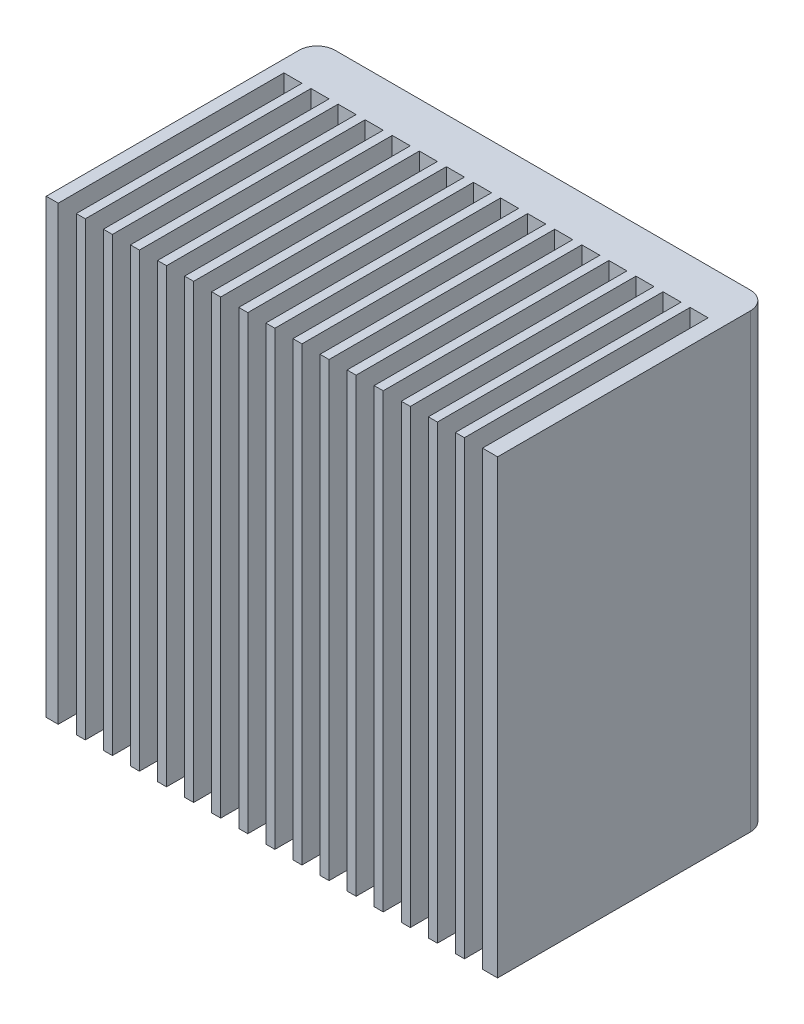
SolidWorks part; units mm, degrees
ref_plane "Front Plane" through (0, 0, 0) normal (0, 0, 1) x (1, 0, 0)
ref_plane "Top Plane" through (0, 0, 0) normal (0, 1, 0) x (1, 0, 0)
ref_plane "Right Plane" through (0, 0, 0) normal (1, 0, 0) x (0, 0, -1)
sketch "Sketch1" plane through (0, 0, 0) normal (0, 0, 1) x (1, 0, 0)
  circle A0 centre (0, 0) radius 10
extrude "Boss-Extrude1" add sketch "Sketch1" along normal blind 1
sketch "Sketch2" plane through (0, 0, 1) normal (0, 0, 1) x (1, 0, 0)
  line L1 (-25, 25) -> (25, 25)
  line L2 (-25, 25) -> (-25, -25)
  line L3 (-25, -25) -> (25, -25)
  line L4 (25, 25) -> (25, -25)
  line L5 (-25, 25) -> (25, -25) construction
  line L6 (-25, -25) -> (25, 25) construction
  point P0 (0, 0)
extrude "Boss-Extrude2" add sketch "Sketch2" along normal blind 30
sketch "Sketch3" plane through (0, 0, 31) normal (0, 0, 1) x (1, 0, 0)
  line L0 (25, 25) -> (-25, 25) construction
  line L1 (-23.6705, 25) -> (-21.6705, 25)
  line L2 (-23.6705, 25) -> (-23.6705, -25)
  line L3 (-23.6705, -25) -> (-21.6705, -25)
  line L4 (-21.6705, 25) -> (-21.6705, -25)
  line L5 (-25, -25) -> (25, -25) construction
  line L6 (-20.6705, 25) -> (-18.6705, 25)
  line L7 (-18.6705, 25) -> (-18.6705, -25)
  line L8 (-20.6705, 25) -> (-20.6705, -25)
  line L9 (-20.6705, -25) -> (-18.6705, -25)
  line L10 (-17.6705, 25) -> (-15.6705, 25)
  line L11 (-15.6705, 25) -> (-15.6705, -25)
  line L12 (-17.6705, 25) -> (-17.6705, -25)
  line L13 (-17.6705, -25) -> (-15.6705, -25)
  line L14 (-14.6705, 25) -> (-12.6705, 25)
  line L15 (-12.6705, 25) -> (-12.6705, -25)
  line L16 (-14.6705, 25) -> (-14.6705, -25)
  line L17 (-14.6705, -25) -> (-12.6705, -25)
  line L18 (-11.6705, 25) -> (-9.6705, 25)
  line L19 (-9.6705, 25) -> (-9.6705, -25)
  line L20 (-11.6705, 25) -> (-11.6705, -25)
  line L21 (-11.6705, -25) -> (-9.6705, -25)
  line L22 (-8.6705, 25) -> (-6.6705, 25)
  line L23 (-6.6705, 25) -> (-6.6705, -25)
  line L24 (-8.6705, 25) -> (-8.6705, -25)
  line L25 (-8.6705, -25) -> (-6.6705, -25)
  line L26 (-5.6705, 25) -> (-3.6705, 25)
  line L27 (-3.6705, 25) -> (-3.6705, -25)
  line L28 (-5.6705, 25) -> (-5.6705, -25)
  line L29 (-5.6705, -25) -> (-3.6705, -25)
  line L30 (-2.6705, 25) -> (-0.6705, 25)
  line L31 (-0.6705, 25) -> (-0.6705, -25)
  line L32 (-2.6705, 25) -> (-2.6705, -25)
  line L33 (-2.6705, -25) -> (-0.6705, -25)
  line L34 (0.3295, 25) -> (2.3295, 25)
  line L35 (2.3295, 25) -> (2.3295, -25)
  line L36 (0.3295, 25) -> (0.3295, -25)
  line L37 (0.3295, -25) -> (2.3295, -25)
  line L38 (3.3295, 25) -> (5.3295, 25)
  line L39 (5.3295, 25) -> (5.3295, -25)
  line L40 (3.3295, 25) -> (3.3295, -25)
  line L41 (3.3295, -25) -> (5.3295, -25)
  line L42 (6.3295, 25) -> (8.3295, 25)
  line L43 (8.3295, 25) -> (8.3295, -25)
  line L44 (6.3295, 25) -> (6.3295, -25)
  line L45 (6.3295, -25) -> (8.3295, -25)
  line L46 (9.3295, 25) -> (11.3295, 25)
  line L47 (11.3295, 25) -> (11.3295, -25)
  line L48 (9.3295, 25) -> (9.3295, -25)
  line L49 (9.3295, -25) -> (11.3295, -25)
  line L50 (12.3295, 25) -> (14.3295, 25)
  line L51 (14.3295, 25) -> (14.3295, -25)
  line L52 (12.3295, 25) -> (12.3295, -25)
  line L53 (12.3295, -25) -> (14.3295, -25)
  line L54 (15.3295, 25) -> (17.3295, 25)
  line L55 (17.3295, 25) -> (17.3295, -25)
  line L56 (15.3295, 25) -> (15.3295, -25)
  line L57 (15.3295, -25) -> (17.3295, -25)
  line L58 (18.3295, 25) -> (20.3295, 25)
  line L59 (20.3295, 25) -> (20.3295, -25)
  line L60 (18.3295, 25) -> (18.3295, -25)
  line L61 (18.3295, -25) -> (20.3295, -25)
  line L62 (21.3295, 25) -> (23.3295, 25)
  line L63 (23.3295, 25) -> (23.3295, -25)
  line L64 (21.3295, 25) -> (21.3295, -25)
  line L65 (21.3295, -25) -> (23.3295, -25)
  dimension "D1" = 16
extrude "Cut-Extrude1" cut sketch "Sketch3" against normal blind 25
fillet "Fillet1" radius 2 2 edges at (25, 0, 1) (-25, 0, 1)
